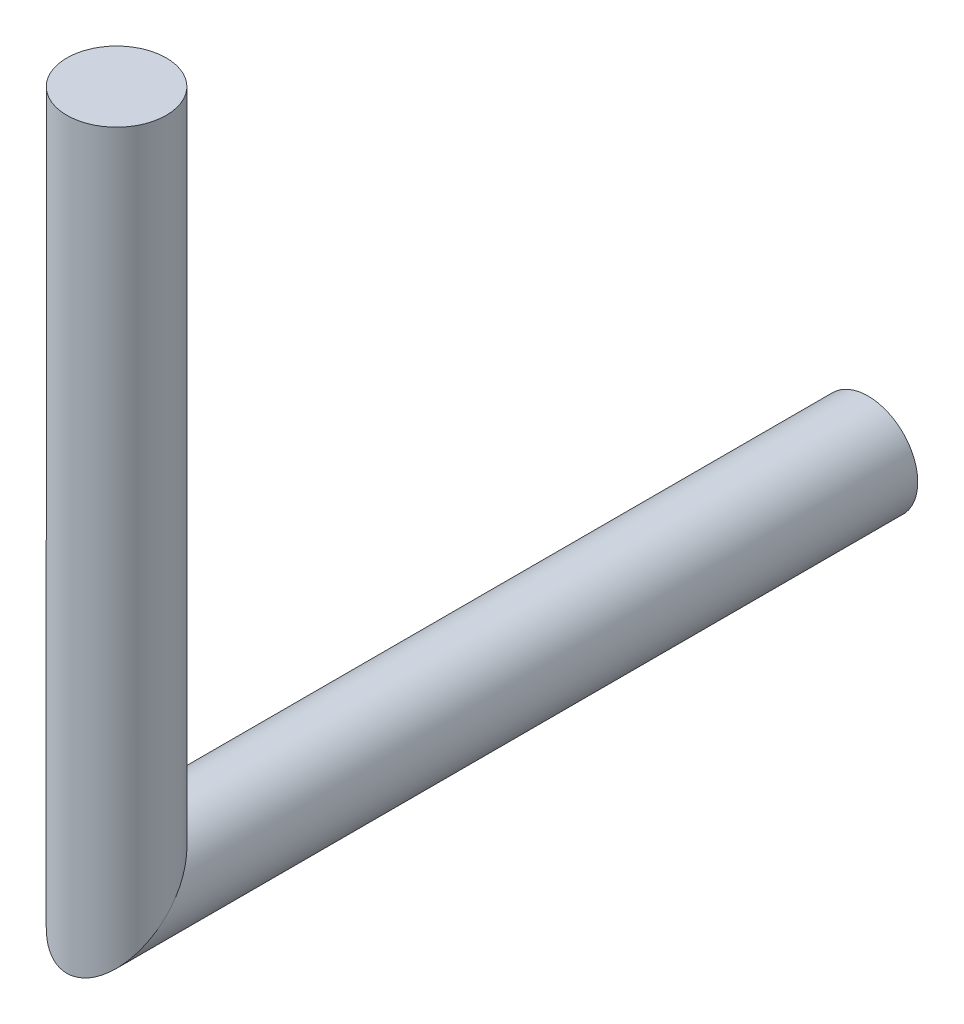
SolidWorks part; units mm, degrees
ref_plane "前视基准面" through (0, 0, 0) normal (0, 0, 1) x (1, 0, 0)
ref_plane "上视基准面" through (0, 0, 0) normal (0, 1, 0) x (1, 0, 0)
ref_plane "右视基准面" through (0, 0, 0) normal (1, 0, 0) x (0, 0, -1)
other "Configuration Table"
sketch "草图1" plane through (0, 0, 0) normal (0, 1, 0) x (1, 0, 0)
  line L0 (0, 0) -> (0, 75.547)
sketch "草图2" plane through (0, 0, 0) normal (0, 0, 1) x (1, 0, 0)
  line L0 (0, 0) -> (0, 69.7089)
curve "组合曲线1"
sweep "扫描2" add path "组合曲线1" circular profile diameter 10 parameters "D3"=10
